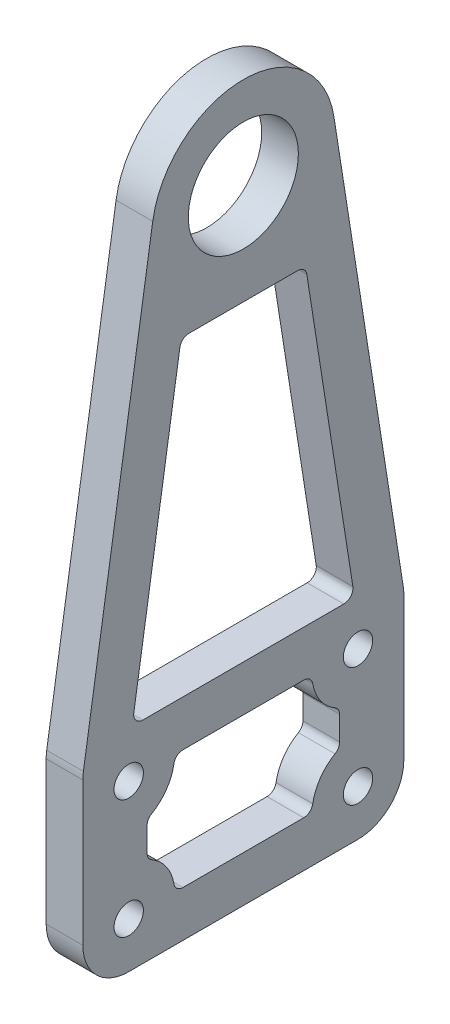
SolidWorks part; units mm, degrees
material "Thornel Mat VMA"
ref_plane "前视基准面" through (0, 0, 0) normal (0, 0, 1) x (1, 0, 0)
ref_plane "上视基准面" through (0, 0, 0) normal (0, 1, 0) x (1, 0, 0)
ref_plane "右视基准面" through (0, 0, 0) normal (1, 0, 0) x (0, 0, -1)
sketch "草图1" plane through (0, 0, 0) normal (1, 0, 0) x (0, 0, -1)
  line L0 (-17.5, -47) -> (-17.5, -68)
  line L1 (-12.5, -50) -> (12.5, -50) construction
  line L2 (-12.5, -50) -> (-12.5, -63) construction
  line L3 (-12.5, -63) -> (12.5, -63) construction
  line L4 (12.5, -50) -> (12.5, -63) construction
  line L5 (-17.5, -68) -> (17.5, -68)
  line L6 (17.5, -68) -> (17.5, -47)
  line L8 (-17.5, -47) -> (-9.879, 1.5507)
  line L9 (17.5, -47) -> (9.879, 1.5507)
  circle A0 centre (0, 0) radius 6
  circle A1 centre (-12.5, -50) radius 1.6
  circle A2 centre (12.5, -50) radius 1.6
  circle A3 centre (-12.5, -63) radius 1.6
  circle A4 centre (12.5, -63) radius 1.6
  arc A5 (-9.879, 1.5507) -> (9.879, 1.5507) centre (0, 0) cw
  point P10 (0, -50)
  dimension "D1" = 12
  dimension "D4" = 3.2
  dimension "D9" = 10
  dimension "D2" = 13
  dimension "D3" = 25
  dimension "D5" = 50
  dimension "D6" = 5
  dimension "D7" = 5
  dimension "D8" = 5
  dimension "D11" = 3
extrude "凸台-拉伸1" add sketch "草图1" along normal blind 4
sketch "草图3" plane through (4, 0, 0) normal (1, 0, 0) x (0, 0, -1)
  line L15 (-6.9205, -11.8449) -> (-11.9435, -43.8449)
  line L16 (-10.9556, -45) -> (10.9556, -45)
  line L17 (11.9435, -43.8449) -> (6.9205, -11.8449)
  line L18 (5.9326, -11) -> (-5.9326, -11)
  line L19 (-9.879, 1.5507) -> (-17.5, -47) construction
  line L20 (17.5, -47) -> (9.879, 1.5507) construction
  line L21 (-10.5, -55.1962) -> (-10.5, -57.8038)
  line L22 (-6.5839, -50) -> (6.5839, -50)
  line L23 (10.5, -55.1962) -> (10.5, -57.8038)
  line L24 (6.5839, -63) -> (-6.5839, -63)
  circle A0 centre (12.5, -50) radius 1.6 construction
  arc A1 (-7.5699, -50.8333) -> (-10, -54.3301) centre (-12.5, -50) cw
  arc A2 (7.5699, -50.8333) -> (10, -54.3301) centre (12.5, -50) ccw
  arc A3 (10, -58.6699) -> (7.5699, -62.1667) centre (12.5, -63) ccw
  arc A4 (-10, -58.6699) -> (-7.5699, -62.1667) centre (-12.5, -63) cw
  circle A5 centre (-12.5, -50) radius 1.6 construction
  arc A6 (7.5699, -50.8333) -> (6.5839, -50) centre (6.5839, -51) ccw
  arc A7 (10, -54.3301) -> (10.5, -55.1962) centre (9.5, -55.1962) cw
  arc A8 (10, -58.6699) -> (10.5, -57.8038) centre (9.5, -57.8038) ccw
  arc A9 (7.5699, -62.1667) -> (6.5839, -63) centre (6.5839, -62) cw
  arc A10 (-7.5699, -62.1667) -> (-6.5839, -63) centre (-6.5839, -62) ccw
  arc A11 (-10, -58.6699) -> (-10.5, -57.8038) centre (-9.5, -57.8038) cw
  arc A12 (-10, -54.3301) -> (-10.5, -55.1962) centre (-9.5, -55.1962) ccw
  arc A13 (-7.5699, -50.8333) -> (-6.5839, -50) centre (-6.5839, -51) cw
  arc A20 (-6.9205, -11.8449) -> (-5.9326, -11) centre (-5.9326, -12) cw
  arc A21 (6.9205, -11.8449) -> (5.9326, -11) centre (5.9326, -12) ccw
  arc A22 (10.9556, -45) -> (11.9435, -43.8449) centre (10.9556, -44) ccw
  arc A23 (-11.9435, -43.8449) -> (-10.9556, -45) centre (-10.9556, -44) ccw
  dimension "D12" = 5
  dimension "D15" = 1
  dimension "D2" = 1
  dimension "D3" = 11
  dimension "D9" = 5
  dimension "D10" = 5
  dimension "D11" = 5
  dimension "D13" = 2
  dimension "D14" = 2
extrude "切除-拉伸2" cut sketch "草图3" against normal through all
fillet "圆角1" radius 5 4 edges at (2, -47, 17.5) (2, -47, -17.5) (2, -68, -17.5) (2, -68, 17.5)
